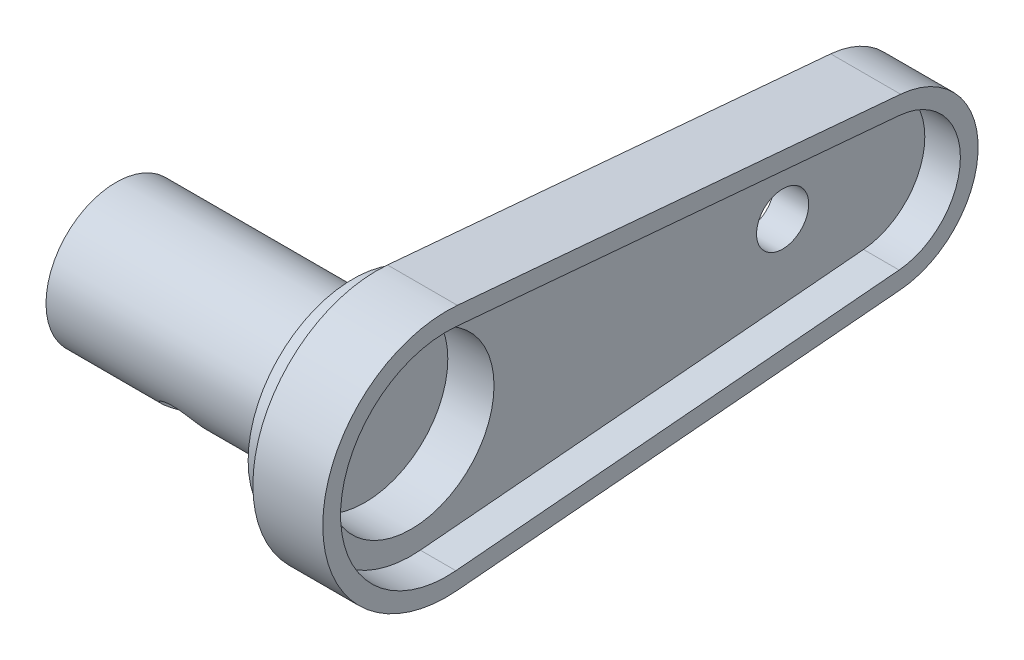
SolidWorks part; units mm, degrees
ref_plane "Front Plane" through (0, 0, 0) normal (0, 0, 1) x (1, 0, 0)
ref_plane "Top Plane" through (0, 0, 0) normal (0, 1, 0) x (1, 0, 0)
ref_plane "Right Plane" through (0, 0, 0) normal (1, 0, 0) x (0, 0, -1)
sketch "Sketch1" plane through (0, 0, 0) normal (1, 0, 0) x (0, 0, -1)
  line L0 (0, -5.3086) -> (0, 5.3086) construction
  line L1 (28.0924, -3.3356) -> (28.0924, 3.3356) construction
  line L2 (24.7695, 3.6263) -> (5.7713, 5.2884)
  line L3 (24.7695, -3.6263) -> (5.7713, -5.2884)
  line L4 (-3.2673, 0) -> (38.3183, 0) construction
  line L6 (0, -10.9604) -> (0, 17.3539) construction
  line L8 (28.0924, -10.9604) -> (28.0924, 17.3539) construction
  line L9 (5.3086, -5.3086) -> (5.3086, 5.3086) construction
  arc A0 (5.7713, 5.2884) -> (5.7713, -5.2884) centre (5.3086, 0) ccw
  arc A1 (24.7695, -3.6263) -> (24.7695, 3.6263) centre (24.4523, 0) ccw
  dimension "D2" = 10.6172
  dimension "D3" = 5
  dimension "D5" = 5
  dimension "D1" = 28.0924
  dimension "D4" = 5.3086
extrude "Boss-Extrude1" add sketch "Sketch1" along normal blind 2.9972
sketch "Sketch2" plane through (0, 0, 0) normal (-1, 0, 0) x (0, 0, 1)
  circle A0 centre (-5.3086, 0) radius 3
  dimension "D1" = 6
extrude "Boss-Extrude2" add sketch "Sketch2" along normal blind 11.176
sketch "Sketch3" plane through (0, 0, 0) normal (-1, 0, 0) x (0, 0, 1)
  circle A0 centre (-5.3086, 0) radius 4.4958
  dimension "D1" = 8.9916
extrude "Boss-Extrude3" add sketch "Sketch3" along normal blind 1.016
sketch "Sketch4" plane through (2.9972, 0, 0) normal (1, 0, 0) x (0, 0, -1)
  line L0 (24.7695, 3.6263) -> (5.7713, 5.2884) construction
  line L1 (5.7713, -5.2884) -> (24.7695, -3.6263) construction
  line L2 (24.7695, 3.6263) -> (5.7713, 5.2884) construction
  line L3 (5.7713, -5.2884) -> (24.7695, -3.6263) construction
  line L4 (24.7031, 2.8672) -> (5.7049, 4.5293)
  line L5 (5.7049, -4.5293) -> (24.7031, -2.8672)
  arc A0 (5.7713, 5.2884) -> (5.7713, -5.2884) centre (5.3086, 0) ccw construction
  arc A1 (24.7695, -3.6263) -> (24.7695, 3.6263) centre (24.4523, 0) ccw construction
  arc A2 (5.7713, 5.2884) -> (5.7713, -5.2884) centre (5.3086, 0) ccw construction
  arc A3 (24.7695, -3.6263) -> (24.7695, 3.6263) centre (24.4523, 0) ccw construction
  arc A4 (5.7049, 4.5293) -> (5.7049, -4.5293) centre (5.3086, 0) ccw
  arc A5 (24.7031, -2.8672) -> (24.7031, 2.8672) centre (24.4523, 0) ccw
  dimension "D1" = 0.762
extrude "Cut-Extrude1" cut sketch "Sketch4" against normal blind 1.524
sketch "Sketch5" plane through (1.4732, 0, 0) normal (1, 0, 0) x (0, 0, -1)
  circle A0 centre (5.3086, 0) radius 3.556
  dimension "D1" = 7.112
extrude "Cut-Extrude2" cut sketch "Sketch5" against normal blind 1.9812
sketch "Sketch6" plane through (1.4732, 0, 0) normal (1, 0, 0) x (0, 0, -1)
  line L0 (-1.2213, 0) -> (32.579, 0) construction
  line L1 (28.0924, 0) -> (28.0924, 4.7193) construction
  line L2 (22.352, 0) -> (22.352, 4.7193) construction
  line L3 (21.2344, 0) -> (21.2344, 4.7193) construction
  arc A0 (24.7695, -3.6263) -> (24.7695, 3.6263) centre (24.4523, 0) ccw construction
  circle A1 centre (21.2344, 0) radius 1.1176
  dimension "D3" = 2.2352
  dimension "D1" = 5.7404
  dimension "D2" = 1.1176
extrude "Cut-Extrude3" cut sketch "Sketch6" against normal through all
sketch "Sketch8" plane through (2.9972, 0, 0) normal (1, 0, 0) x (0, 0, -1)
  line L0 (5.3086, 0) -> (24.4523, 0) construction
sketch "Sketch9" plane through (0, 4.9434, -8.5623) normal (0, 0.5, -0.866) x (-1, 0, 0)
  circle A0 centre (6.1341, -3.622) radius 0.9906 construction
  circle A1 centre (6.1341, -3.622) radius 0.9906
extrude "Cut-Extrude4" cut sketch "Sketch9" against normal blind 10.16
scale "Scale1" scale about centroid uniform scaling yes scale factor 0.6
